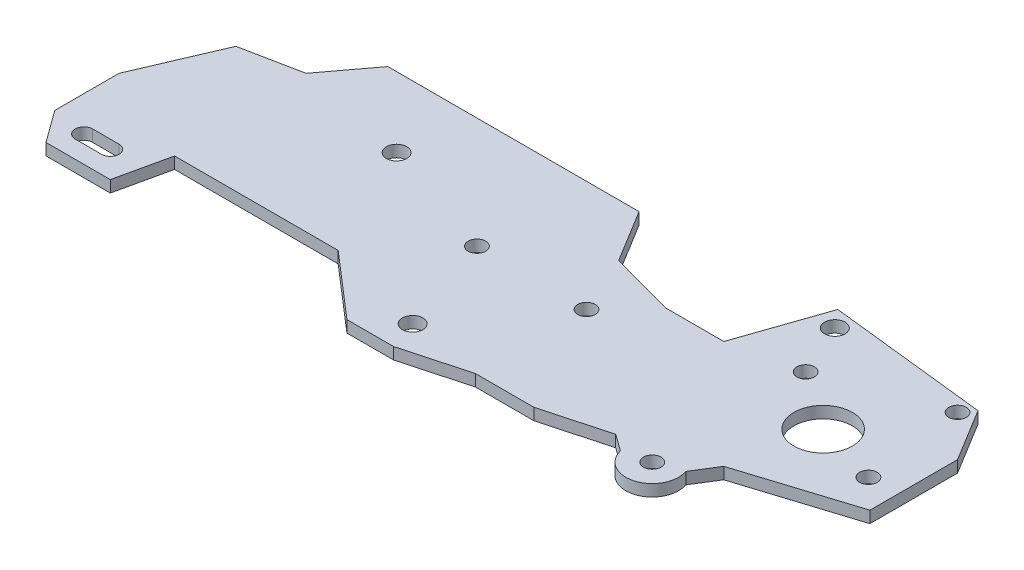
SolidWorks part; units mm, degrees
material "1060 Alloy"
ref_plane "Front Plane" through (0, 0, 0) normal (0, 0, 1) x (1, 0, 0)
ref_plane "Top Plane" through (0, 0, 0) normal (0, 1, 0) x (1, 0, 0)
ref_plane "Right Plane" through (0, 0, 0) normal (1, 0, 0) x (0, 0, -1)
sketch "Sketch1" plane through (0, 0, 0) normal (0, 1, 0) x (1, 0, 0)
  line L0 (0, 0) -> (43, 0)
  line L1 (43, 0) -> (48.5, -9)
  line L2 (48.5, -9) -> (59.5, -12)
  line L3 (59.5, -12) -> (69.5, -12)
  line L4 (69.5, -12) -> (74.5, 2.5)
  line L5 (74.5, 2.5) -> (101.5, -0.5)
  line L6 (101.5, -0.5) -> (107, -9.5)
  line L7 (107, -9.5) -> (107, -24.5)
  line L8 (107, -24.5) -> (88, -30.5)
  line L9 (88, -30.5) -> (85.5, -34.5)
  line L10 (0, 0) -> (-6, -8)
  line L11 (-6, -8) -> (-16, -10)
  line L12 (-16, -10) -> (-22, -24)
  line L13 (-22, -24) -> (-22, -35)
  line L14 (-22, -35) -> (-18, -40.5)
  line L15 (-18, -40.5) -> (-7, -40.5)
  line L16 (-7, -40.5) -> (-5, -31.5)
  line L17 (-5, -31.5) -> (23, -31.5)
  line L18 (23, -31.5) -> (34, -41)
  line L19 (34, -41) -> (42, -41)
  line L20 (42, -41) -> (53, -38)
  line L21 (53, -38) -> (63, -38)
  line L22 (63, -38) -> (74, -35)
  line L23 (74, -35) -> (76.8704, -37.0637)
  line L24 (-16, -34.5) -> (-11.5, -34.5)
  line L25 (-16, -37.5) -> (-11.5, -37.5)
  circle A0 centre (40.25, -36) radius 1.75
  circle A1 centre (81.25, -36) radius 1.5
  arc A2 (76.8704, -37.0637) -> (85.5, -34.5) centre (81.25, -36) ccw
  arc A3 (-11.5, -37.5) -> (-11.5, -34.5) centre (-11.5, -36) ccw
  arc A4 (-16, -34.5) -> (-16, -37.5) centre (-16, -36) ccw
  circle A5 centre (91, -16.5) radius 5
  circle A6 centre (77, -0.5) radius 1.75
  circle A7 centre (81, -9.5) radius 1.5
  circle A8 centre (100, -2.5) radius 1.5
  circle A9 centre (102, -19.75) radius 1.5
  circle A10 centre (53, -19) radius 1.5
  circle A11 centre (34.25, -19) radius 1.5
  circle A12 centre (13.5, -12) radius 1.75
  dimension "D39" = 3.5
  dimension "D40" = 5
  dimension "D41" = 6.25
  dimension "D42" = 3
  dimension "D43" = 41
  dimension "D44" = 6.5
  dimension "D45" = 6
  dimension "D46" = 10
  dimension "D47" = 16
  dimension "D48" = 8
  dimension "D49" = 3.5
  dimension "D50" = 3
  dimension "D51" = 2.5
  dimension "D52" = 3
  dimension "D53" = 1.5
  dimension "D54" = 1.5
  dimension "D55" = 4
  dimension "D56" = 9
  dimension "D57" = 3
  dimension "D58" = 7
  dimension "D59" = 2
  dimension "D60" = 3
  dimension "D61" = 5
  dimension "D62" = 17.25
  dimension "D63" = 3
  dimension "D64" = 16.5
  dimension "D65" = 7
  dimension "D66" = 3
  dimension "D67" = 18.75
  dimension "D68" = 3.5
  dimension "D69" = 12
  dimension "D70" = 20.75
  dimension "D1" = 43
  dimension "D2" = 9
  dimension "D3" = 5.5
  dimension "D4" = 11
  dimension "D5" = 3
  dimension "D6" = 10
  dimension "D7" = 14.5
  dimension "D8" = 5
  dimension "D9" = 27
  dimension "D10" = 3
  dimension "D11" = 5.5
  dimension "D12" = 9
  dimension "D13" = 15
  dimension "D14" = 19
  dimension "D15" = 6
  dimension "D16" = 2.5
  dimension "D17" = 4
  dimension "D18" = 6
  dimension "D19" = 8
  dimension "D20" = 10
  dimension "D21" = 2
  dimension "D22" = 14
  dimension "D23" = 6
  dimension "D24" = 11
  dimension "D25" = 5.5
  dimension "D26" = 4
  dimension "D27" = 11
  dimension "D28" = 9
  dimension "D29" = 2
  dimension "D30" = 28
  dimension "D31" = 9.5
  dimension "D32" = 11
  dimension "D33" = 8
  dimension "D34" = 3
  dimension "D35" = 11
  dimension "D36" = 10
  dimension "D37" = 3
  dimension "D38" = 11
extrude "Boss-Extrude1" add sketch "Sketch1" along normal blind 2
